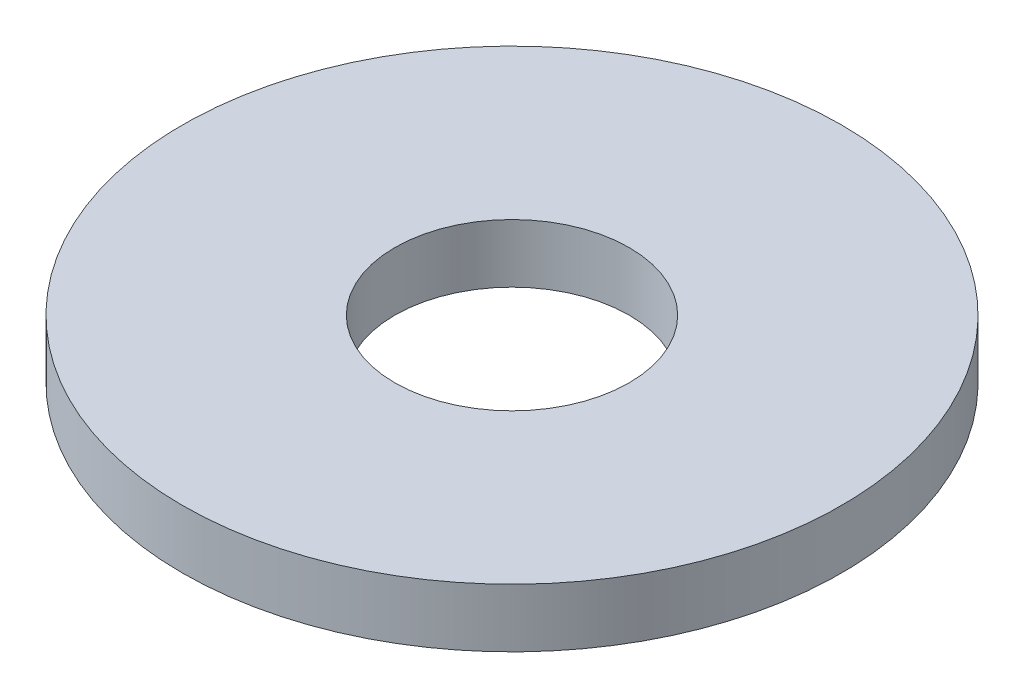
SolidWorks part; units mm, degrees
material "Cast Stainless Steel"
ref_plane "Front Plane" through (0, 0, 0) normal (0, 0, 1) x (1, 0, 0)
ref_plane "Top Plane" through (0, 0, 0) normal (0, 1, 0) x (1, 0, 0)
ref_plane "Right Plane" through (0, 0, 0) normal (1, 0, 0) x (0, 0, -1)
sketch "Sketch1" plane through (0, 0, 0) normal (0, 1, 0) x (1, 0, 0)
  circle A0 centre (0, 0) radius 1.6
  circle A1 centre (0, 0) radius 4.5
  dimension "D1" = 3.2
  dimension "D2" = 9
extrude "Boss-Extrude1" add sketch "Sketch1" along normal blind 0.8
equation "\"d1\"= 3.2"
equation "\"d2\"= 9"
equation "\"s\"= 0.8"
equation "\"D2@Sketch1\"=\"d2\""
equation "\"D1@Sketch1\"=\"d1\""
equation "\"D1@Boss-Extrude1\"=\"s\""
